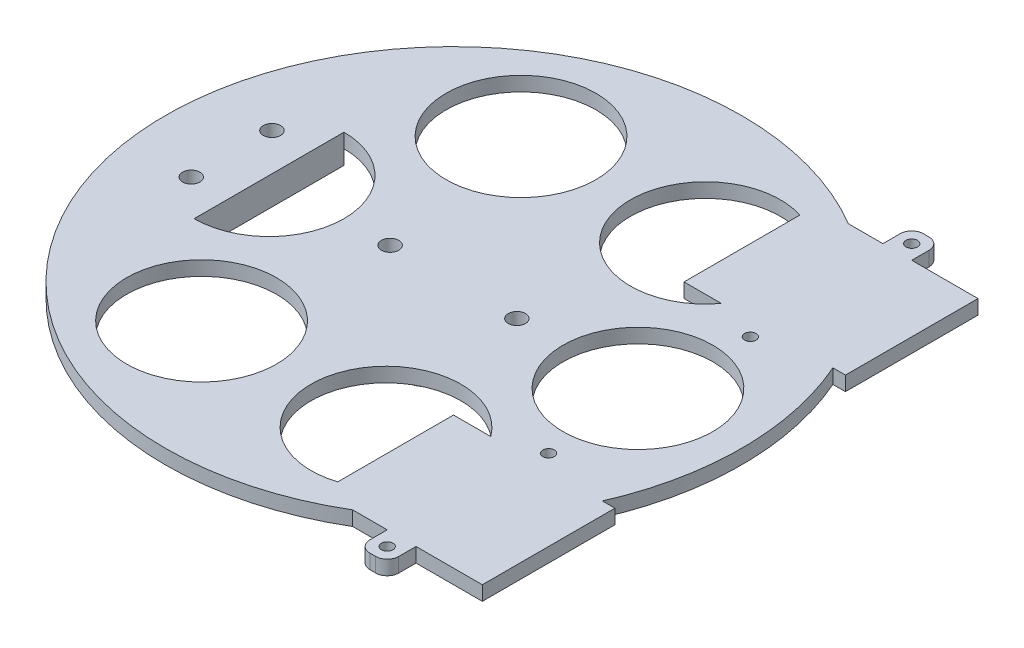
SolidWorks part; units mm, degrees
ref_plane "前视基准面" through (0, 0, 0) normal (0, 0, 1) x (1, 0, 0)
ref_plane "上视基准面" through (0, 0, 0) normal (0, 1, 0) x (1, 0, 0)
ref_plane "右视基准面" through (0, 0, 0) normal (1, 0, 0) x (0, 0, -1)
sketch "草图1" plane through (0, 0, 0) normal (0, 1, 0) x (1, 0, 0)
  circle A0 centre (0, 0) radius 50
  dimension "D1" = 100
extrude "凸台-拉伸1" add sketch "草图1" along normal blind 2.5
sketch "草图2" plane through (0, 0, 0) normal (0, -1, 0) x (-1, 0, 0)
  circle A0 centre (0, 0) radius 15
  dimension "D1" = 30
extrude "凸台-拉伸2" add sketch "草图2" along normal blind 3
sketch "草图3" plane through (0, -3, 0) normal (0, -1, 0) x (-1, 0, 0)
  circle A0 centre (11, 0) radius 1.5
  circle A1 centre (0, 0) radius 15 construction
  circle A2 centre (-11, 0) radius 1.5
  dimension "D1" = 3
  dimension "D3" = 3
  dimension "D2" = 11
  dimension "D4" = 11
extrude "切除-拉伸1" cut sketch "草图3" against normal through all
sketch "草图5" plane through (0, 0, 0) normal (0, -1, 0) x (-1, 0, 0)
  circle A0 centre (32, 0) radius 13
  circle A1 centre (0, 0) radius 50 construction
  circle A2 centre (16, -27.7128) radius 13
  circle A3 centre (-16, -27.7128) radius 13
  circle A4 centre (-32, 0) radius 13
  circle A5 centre (-16, 27.7128) radius 13
  circle A6 centre (16, 27.7128) radius 13
  point P17 (0, 0)
  dimension "D1" = 26
  dimension "D2" = 32
  dimension "D3" = 6
extrude "切除-拉伸3" cut sketch "草图5" against normal through all
sketch "草图6" plane through (0, 0, 0) normal (0, -1, 0) x (-1, 0, 0)
  line L1 (32, -13) -> (45, -13)
  line L2 (32, -13) -> (32, 13)
  line L3 (32, 13) -> (45, 13)
  line L4 (45, -13) -> (45, 13)
  circle A0 centre (32, 0) radius 13 construction
extrude "凸台-拉伸3" add sketch "草图6" against normal mid plane 5
sketch "草图8" plane through (0, -2.5, 0) normal (0, -1, 0) x (-1, 0, 0)
  line L0 (32, -13) -> (45, -13) construction
  line L1 (45, 13) -> (32, 13) construction
  circle A0 centre (38.5, -7) radius 1.5
  circle A1 centre (38.5, 7) radius 1.5
  dimension "D1" = 3
  dimension "D2" = 3
  dimension "D3" = 6
  dimension "D4" = 6
extrude "切除-拉伸4" cut sketch "草图8" against normal through all
sketch "草图9" plane through (0, 0, 0) normal (0, -1, 0) x (-1, 0, 0)
  line L0 (-36.5, -43) -> (-48, -43)
  line L1 (-20, -43) -> (-31.5, -43)
  line L2 (-20, -43) -> (-20, -20)
  line L3 (-20, -20) -> (-48, -20)
  line L4 (-48, -43) -> (-48, -20)
  line L5 (0, 0) -> (-54.5048, 0) construction
  line L6 (-31.5, -43) -> (-31.5, -48)
  line L7 (-31.5, -48) -> (-36.5, -48)
  line L8 (-36.5, -43) -> (-36.5, -48)
  line L9 (-31.5, 43) -> (-31.5, 48)
  line L10 (-31.5, 48) -> (-36.5, 48)
  line L11 (-36.5, 43) -> (-36.5, 48)
  line L12 (-36.5, 43) -> (-48, 43)
  line L13 (-20, 43) -> (-31.5, 43)
  line L14 (-20, 43) -> (-20, 20)
  line L15 (-20, 20) -> (-48, 20)
  line L16 (-48, 43) -> (-48, 20)
  circle A0 centre (0, 0) radius 50 construction
  dimension "D1" = 28
  dimension "D2" = 23
  dimension "D3" = 20
  dimension "D4" = 20
  dimension "D5" = 5
  dimension "D6" = 5
  dimension "D7" = 11.5
extrude "凸台-拉伸4" add sketch "草图9" against normal blind 2.5
sketch "草图11" plane through (0, 0, 0) normal (0, -1, 0) x (-1, 0, 0)
  line L0 (0, 0) -> (-61.687, 0) construction
  circle A0 centre (-34, -45.5) radius 1
  circle A1 centre (-34, -17.5) radius 1
  circle A2 centre (-34, 17.5) radius 1
  circle A3 centre (-34, 45.5) radius 1
  dimension "D1" = 2
  dimension "D2" = 2
  dimension "D3" = 28
extrude "切除-拉伸5" cut sketch "草图11" against normal through all
fillet "圆角1" radius 2 4 edges at (36.5, 1.25, 48) (31.5, 1.25, 48) (36.5, 1.25, -48) (31.5, 1.25, -48)
